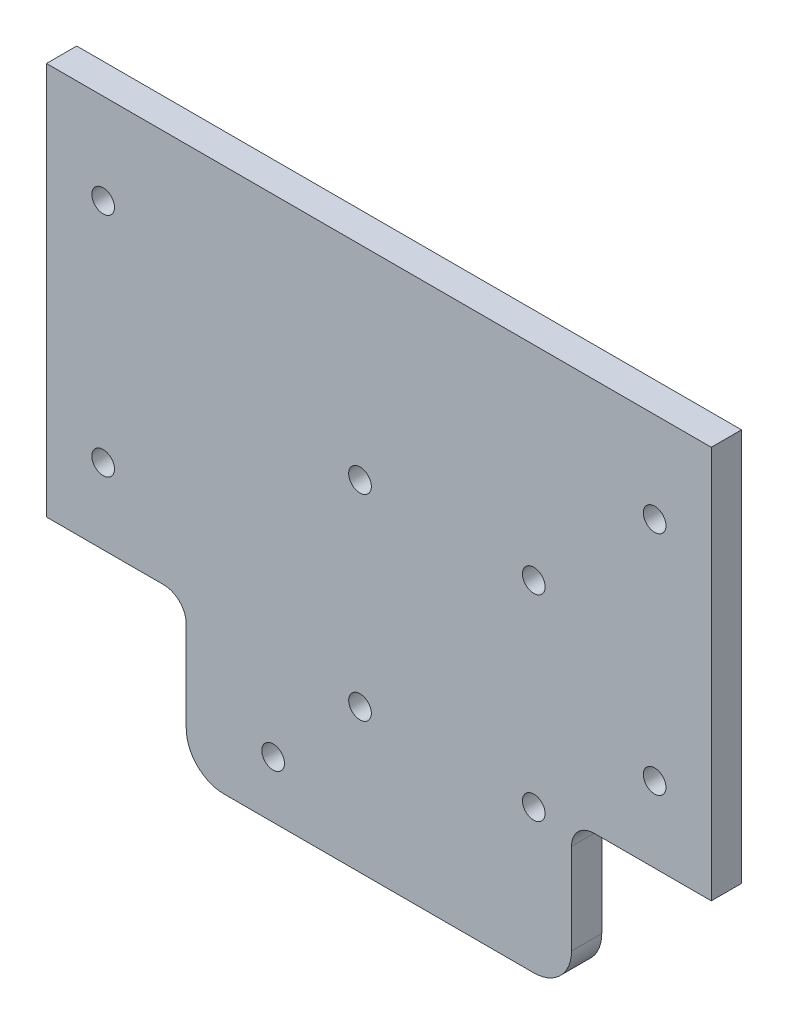
SolidWorks part; units mm, degrees
material "Thornel Mat VMA"
ref_plane "前视基准面" through (0, 0, 0) normal (0, 0, 1) x (1, 0, 0)
ref_plane "上视基准面" through (0, 0, 0) normal (0, 1, 0) x (1, 0, 0)
ref_plane "右视基准面" through (0, 0, 0) normal (1, 0, 0) x (0, 0, -1)
sketch "草图1" plane through (0, 0, 0) normal (0, 0, 1) x (1, 0, 0)
  line L1 (0, 0) -> (88, 0)
  line L2 (0, 0) -> (0, 72)
  line L3 (0, 72) -> (88, 72)
  line L4 (88, 0) -> (88, 72)
  dimension "D1" = 88
  dimension "D2" = 72
extrude "凸台-拉伸1" add sketch "草图1" along normal blind 4
sketch "草图2" plane through (0, 0, 4) normal (0, 0, 1) x (1, 0, 0)
  line L1 (0, 0) -> (18.5, 0)
  line L2 (0, 0) -> (0, 20)
  line L3 (0, 20) -> (18.5, 20)
  line L4 (18.5, 0) -> (18.5, 20)
  dimension "D1" = 18.5
  dimension "D2" = 20
extrude "切除-拉伸1" cut sketch "草图2" against normal through all
fillet "圆角1" radius 3 1 edges at (18.5, 20, 2)
sketch "草图3" plane through (0, 0, 4) normal (0, 0, 1) x (1, 0, 0)
  line L1 (88, 0) -> (69.5, 0)
  line L2 (88, 0) -> (88, 20)
  line L3 (88, 20) -> (69.5, 20)
  line L4 (69.5, 0) -> (69.5, 20)
  dimension "D1" = 18.5
  dimension "D2" = 20
extrude "切除-拉伸2" cut sketch "草图3" against normal through all
fillet "圆角2" radius 3 1 edges at (69.5, 20, 2)
sketch "草图5" plane through (0, 0, 4) normal (0, 0, 1) x (1, 0, 0)
  line L0 (44, 0) -> (44, 72) construction
  line L1 (88, 72) -> (0, 72) construction
  line L4 (18.5, 7.5) -> (69.5, 7.5) construction
  line L5 (18.5, 0) -> (18.5, 17) construction
  line L6 (69.5, 17) -> (69.5, 0) construction
  line L7 (18.5, 0) -> (69.5, 0) construction
  line L8 (80.5, 72) -> (80.5, 15) construction
  line L11 (88, 20) -> (88, 72) construction
  line L12 (18.5, 0) -> (69.5, 0) construction
  line L13 (88, 72) -> (0, 72) construction
  circle A0 centre (80.5, 60) radius 1.5
  circle A1 centre (80.5, 30) radius 1.5
  circle A3 centre (30, 7.5) radius 1.5
  circle A4 centre (7.5, 30) radius 1.5
  circle A5 centre (7.5, 60) radius 1.5
  dimension "D4" = 30
  dimension "D5" = 3
  dimension "D6" = 3
  dimension "D1" = 30
  dimension "D2" = 7.5
  dimension "D3" = 7.5
  dimension "D7" = 14
extrude "切除-拉伸4" cut sketch "草图5" against normal through all
sketch "草图4" plane through (0, 0, 4) normal (0, 0, 1) x (1, 0, 0)
  line L0 (88, 20) -> (88, 72) construction
  line L1 (41.5, 45) -> (64.5, 45) construction
  line L2 (41.5, 45) -> (41.5, 19) construction
  line L3 (41.5, 19) -> (64.5, 19) construction
  line L4 (64.5, 45) -> (64.5, 19) construction
  line L5 (41.5, 45) -> (64.5, 19) construction
  line L6 (41.5, 19) -> (64.5, 45) construction
  line L8 (88, 72) -> (0, 72) construction
  circle A0 centre (41.5, 45) radius 1.5
  circle A1 centre (64.5, 45) radius 1.5
  circle A2 centre (64.5, 19) radius 1.5
  circle A3 centre (41.5, 19) radius 1.5
  point P0 (53, 32)
  dimension "D1" = 3
  dimension "D2" = 23
  dimension "D3" = 26
  dimension "D4" = 35
  dimension "D5" = 40
extrude "切除-拉伸3" cut sketch "草图4" against normal through all
fillet "圆角4" radius 5 2 edges at (18.5, 0, 2) (69.5, 0, 2)
